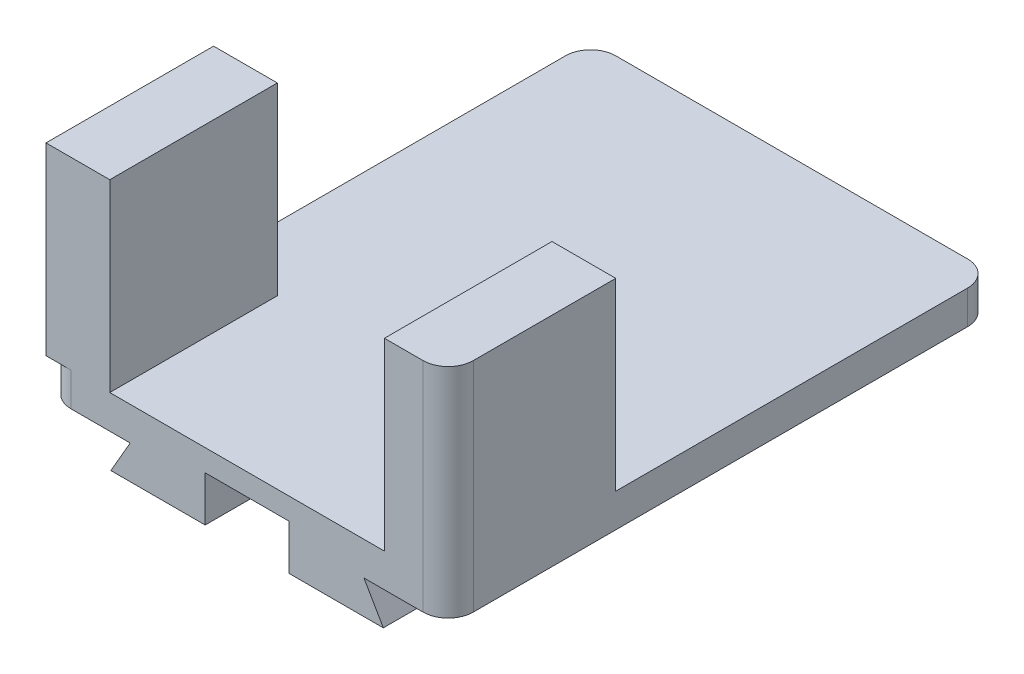
SolidWorks part; units mm, degrees
material "ABS"
ref_plane "Front Plane" through (0, 0, 0) normal (0, 0, 1) x (1, 0, 0)
ref_plane "Top Plane" through (0, 0, 0) normal (0, 1, 0) x (1, 0, 0)
ref_plane "Right Plane" through (0, 0, 0) normal (1, 0, 0) x (0, 0, -1)
sketch "Sketch1" plane through (0, 0, 0) normal (0, 0, 1) x (1, 0, 0)
  line L0 (0, 0) -> (30.48, 0)
  line L1 (30.48, 0) -> (30.48, -5.08)
  line L2 (-30.48, -5.08) -> (-17.7173, -5.08)
  line L3 (17.7173, -5.08) -> (20.6502, -10.16)
  line L5 (-20.6502, -10.16) -> (-17.7173, -5.08)
  line L6 (17.7173, -5.08) -> (30.48, -5.08)
  line L7 (-30.48, -5.08) -> (-30.48, 0)
  line L8 (-30.48, 0) -> (0, 0)
  line L9 (20.6502, -10.16) -> (6.35, -10.16)
  line L10 (6.35, -10.16) -> (6.35, -3.302)
  line L11 (6.35, -3.302) -> (-6.35, -3.302)
  line L12 (-6.35, -3.302) -> (-6.35, -10.16)
  line L13 (-6.35, -10.16) -> (-20.6502, -10.16)
  dimension "D1" = 41.3004
  dimension "D2" = 60.96
  dimension "D3" = 60
  dimension "D4" = 12.7
  dimension "D5" = 5.08
  dimension "D6" = 5.08
  dimension "D7" = 6.858
extrude "Extrude1" add sketch "Sketch1" along normal blind 82.55
sketch "Sketch2" plane through (0, 0, 0) normal (0, 1, 0) x (1, 0, 0)
  line L0 (30.48, 0) -> (-30.48, 0) construction
  line L1 (26.67, 0) -> (20.32, 0)
  line L2 (26.67, 0) -> (26.67, -63.5)
  line L3 (26.67, -63.5) -> (20.32, -63.5)
  line L4 (20.32, 0) -> (20.32, -63.5)
  line L5 (10.16, 0) -> (3.81, 0)
  line L6 (10.16, 0) -> (10.16, -63.5)
  line L7 (10.16, -63.5) -> (3.81, -63.5)
  line L8 (3.81, 0) -> (3.81, -63.5)
  line L9 (30.48, -82.55) -> (30.48, 0) construction
  dimension "D1" = 0
  dimension "D2" = 10.16
  dimension "D3" = 3.81
  dimension "D4" = 63.5
  dimension "D5" = 6.35
extrude "Extrude2" [suppressed] add sketch "Sketch2" along normal blind 27.94
sketch "Sketch3" [suppressed] plane through (3.81, 0, 0) normal (-1, 0, 0) x (0, 0, 1)
  line L0 (10.16, 1.27) -> (0, 1.27) construction
  line L1 (10.16, 1.27) -> (53.34, 1.27)
  line L2 (10.16, 1.27) -> (10.16, 20.955)
  line L3 (10.16, 20.955) -> (53.34, 20.955)
  line L4 (53.34, 1.27) -> (53.34, 20.955)
  line L5 (0, 27.94) -> (0, 0) construction
  line L6 (53.34, 1.27) -> (63.5, 1.27) construction
  line L7 (63.5, 27.94) -> (63.5, 0) construction
  line L8 (0, 0) -> (63.5, 0) construction
  dimension "D1" = 43.18
  dimension "D2" = 1.27
  dimension "D3" = 19.685
extrude "Extrude3" [suppressed] cut sketch "Sketch3" against normal through all
ref_plane "Plane1" [suppressed] through (0, 0, 31.75) normal (0, 0, -1) x (-1, 0, 0)
sketch "Sketch5" plane through (0, 0, 82.55) normal (0, 0, 1) x (1, 0, 0)
  line L0 (-30.48, -5.08) -> (-17.7173, -5.08) construction
  line L1 (-25.4, -5.08) -> (-20.32, -5.08)
  line L2 (-25.4, -5.08) -> (-25.4, 39.37)
  line L3 (-25.4, 39.37) -> (-20.32, 39.37)
  line L4 (-20.32, -5.08) -> (-20.32, 39.37)
  line L5 (30.48, 0) -> (-30.48, 0) construction
  point P9 (0, 0)
  dimension "D1" = 44.45
  dimension "D2" = 5.08
  dimension "D3" = 25.4
sketch "Sketch8" plane through (0, 0, 0) normal (0, 1, 0) x (1, 0, 0)
  line L7 (30.48, -82.55) -> (20.8153, -82.55)
  line L8 (30.48, -82.55) -> (30.48, -57.15)
  line L9 (30.48, -57.15) -> (20.8153, -57.15)
  line L10 (20.8153, -82.55) -> (20.8153, -57.15)
  dimension "D1" = 9.6647
  dimension "D3" = 25.4
extrude "Extrude6" add sketch "Sketch8" along normal blind 27.94
fillet "Fillet1" radius 3.81 4 edges at (30.48, 11.43, 82.55) (30.48, -2.54, 0) (-30.48, -2.54, 82.55) (-30.48, -2.54, 0)
mirror "Mirror1" about plane through (0, 0, 0) normal (1, 0, 0) of "Extrude6"
